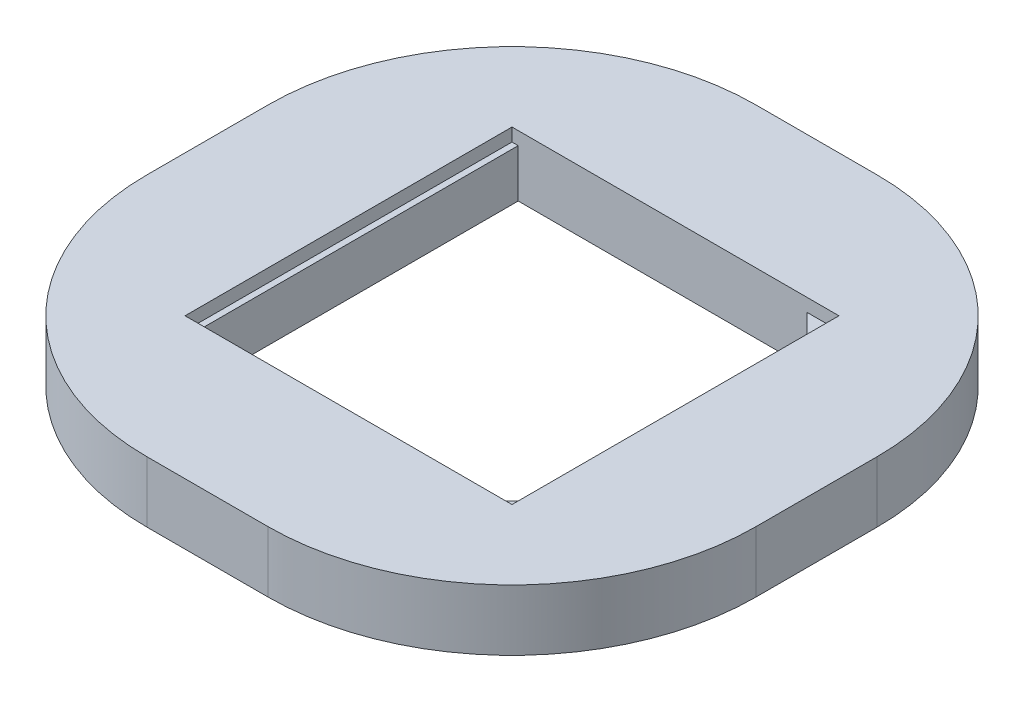
SolidWorks part; units mm, degrees
ref_plane "Front Plane" through (0, 0, 0) normal (0, 0, 1) x (1, 0, 0)
ref_plane "Top Plane" through (0, 0, 0) normal (0, 1, 0) x (1, 0, 0)
ref_plane "Right Plane" through (0, 0, 0) normal (1, 0, 0) x (0, 0, -1)
sketch "Sketch2" plane through (0, 0, 0) normal (0, 1, 0) x (1, 0, 0)
  line L1 (-37.45, -37.45) -> (37.45, -37.45)
  line L2 (-37.45, -37.45) -> (-37.45, 37.45)
  line L3 (-37.45, 37.45) -> (37.45, 37.45)
  line L4 (37.45, -37.45) -> (37.45, 37.45)
  line L5 (-37.45, -37.45) -> (37.45, 37.45) construction
  line L6 (-37.45, 37.45) -> (37.45, -37.45) construction
  point P0 (0, 0)
  dimension "D1" = 74.9
  dimension "D2" = 74.9
extrude "Base" add sketch "Sketch2" along normal blind 7.5
sketch "Sketch3" plane through (0, 7.5, 0) normal (0, 1, 0) x (1, 0, 0)
  line L1 (-20.1, -20.1) -> (20.1, -20.1)
  line L2 (-20.1, -20.1) -> (-20.1, 20.1)
  line L3 (-20.1, 20.1) -> (20.1, 20.1)
  line L4 (20.1, -20.1) -> (20.1, 20.1)
  line L5 (-20.1, -20.1) -> (20.1, 20.1) construction
  line L6 (-20.1, 20.1) -> (20.1, -20.1) construction
  point P0 (0, 0)
  dimension "D1" = 40.2
  dimension "D2" = 40.2
extrude "Slot" cut sketch "Sketch3" against normal blind 1.6
sketch "Sketch4" plane through (0, 5.9, 0) normal (0, 1, 0) x (1, 0, 0)
  line L0 (-19.3365, -20.1) -> (-19.3365, 20.1)
  line L1 (-19.3365, 20.1) -> (16.1907, 20.1)
  line L3 (16.1907, 20.1) -> (20.1, 16.1907)
  line L4 (20.1, 20.1) -> (-20.1, 20.1) construction
  line L5 (20.1, 16.1907) -> (20.1, -16.1907)
  line L6 (20.1, -20.1) -> (20.1, 20.1) construction
  line L9 (-20.1, -20.1) -> (20.1, -20.1) construction
  line L10 (16.1907, -20.1) -> (-19.3365, -20.1)
  line L11 (20.1, -20.1) -> (20.1, 20.1) construction
  line L12 (16.1907, -20.1) -> (20.1, -16.1907)
  line L13 (20.1, 20.1) -> (18.1454, 18.1454) construction
  line L14 (20.1, -20.1) -> (18.1454, -18.1454) construction
  line L15 (19.1227, -19.1227) -> (19.1227, 19.1227) construction
  point P20 (16.1907, -19.8562)
extrude "Cut-Extrude2" cut sketch "Sketch4" against normal up to surface (5.9 mm away) up to face at (0, 0, 0)
fillet "Fillet1" radius 30 4 edges at (37.45, 3.75, -37.45) (37.45, 3.75, 37.45) (-37.45, 3.75, 37.45) (-37.45, 3.75, -37.45)
